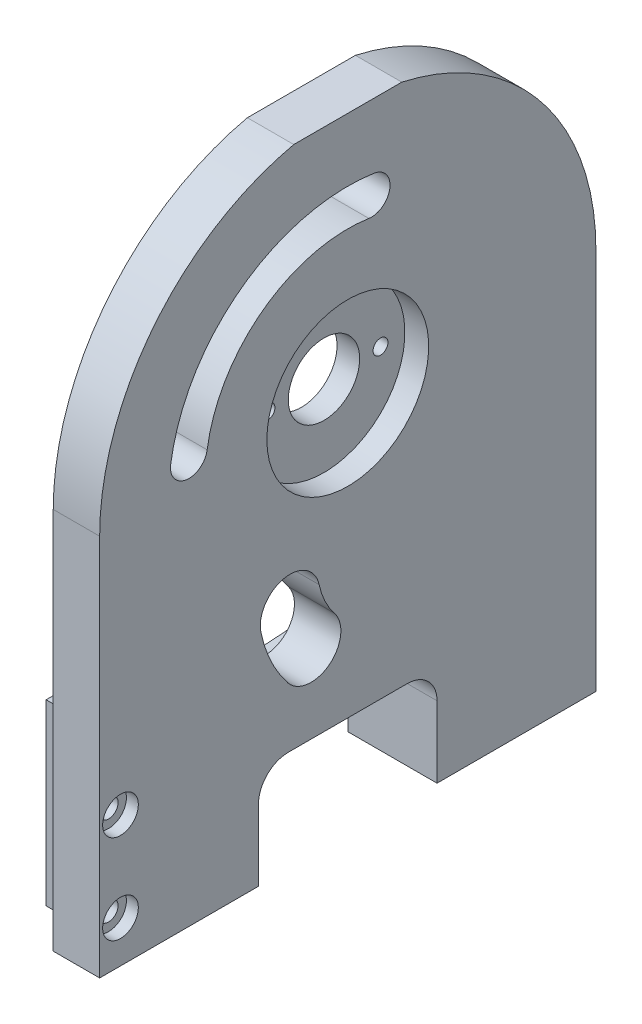
SolidWorks part; units mm, degrees
ref_plane "Front Plane" through (0, 0, 0) normal (0, 0, 1) x (1, 0, 0)
ref_plane "Top Plane" through (0, 0, 0) normal (0, 1, 0) x (1, 0, 0)
ref_plane "Right Plane" through (0, 0, 0) normal (1, 0, 0) x (0, 0, -1)
other "Configuration Table"
sketch "草图1" plane through (0, 0, 0) normal (0, 1, 0) x (1, 0, 0)
  line L0 (0, 0) -> (7.8, 0)
  line L1 (0, 0) -> (0, -83.4)
  line L2 (0, -83.4) -> (7.8, -83.4)
  line L3 (7.8, -83.4) -> (7.8, 0)
extrude "凸台-拉伸1" add sketch "草图1" along normal blind 105
sketch "草图2" plane through (0, 0, 0) normal (-1, 0, 0) x (0, 0, 1)
  line L0 (41.7, 0) -> (41.7, 105) construction
  line L1 (0, 0) -> (83.4, 0) construction
  line L2 (0, 105) -> (83.4, 105) construction
  line L3 (0, 64.3) -> (0, 105)
  line L4 (0, 105) -> (32.6226, 105)
  line L5 (83.4, 105) -> (83.4, 64.3)
  line L6 (50.7774, 105) -> (83.4, 105)
  arc A0 (83.4, 64.3) -> (50.7774, 105) centre (41.7, 64.3) ccw
  arc A1 (32.6226, 105) -> (0, 64.3) centre (41.7, 64.3) ccw
  dimension "D1" = 40.7
extrude "切除-拉伸1" cut sketch "草图2" against normal through all contours L3 L4 A1 | L6 L5 A0
sketch "草图3" plane through (0, 0, 0) normal (-1, 0, 0) x (0, 0, 1)
  line L0 (0, 64.3) -> (83.4, 64.3) construction
  circle A0 centre (41.7, 64.3) radius 6
  dimension "D1" = 12
extrude "切除-拉伸2" cut sketch "草图3" against normal through all
sketch "草图4" plane through (0, 0, 0) normal (-1, 0, 0) x (0, 0, 1)
  circle A0 centre (41.7, 64.3) radius 13.6
extrude "切除-拉伸3" cut sketch "草图4" against normal blind 4
sketch "草图5" plane through (4, 0, 0) normal (-1, 0, 0) x (0, 0, 1)
  line L0 (41.7, 64.3) -> (32.2, 64.3) construction
  line L1 (41.7, 64.3) -> (51.2, 64.3) construction
  circle A0 centre (32.2, 64.3) radius 1.25
  circle A1 centre (51.2, 64.3) radius 1.25
extrude "切除-拉伸4" cut sketch "草图5" against normal blind 4
sketch "草图6" plane through (7.8, 0, 0) normal (1, 0, 0) x (0, 0, -1)
  line L0 (-41.7, 64.3) -> (-41.7, 0) construction
  line L1 (-83.4, 0) -> (0, 0) construction
  line L2 (-83.4, 0) -> (0, 0)
  line L3 (0, 0) -> (0, 30)
  line L6 (-83.4, 30) -> (-69.2536, 30)
  line L7 (-83.4, 30) -> (-83.4, 0)
  line L9 (-14.1464, 30) -> (0, 30)
  arc A0 (-69.2536, 30) -> (-14.1464, 30) centre (-41.7, 61.3) ccw
  line M13 (-83.4, 64.3) -> (-83.4, 0)
  line M14 (-83.4, 0) -> (0, 0)
  line M15 (0, 0) -> (0, 64.3)
  dimension "D1" = 3
  dimension "D2" = 30
extrude "凸台-拉伸2" add sketch "草图6" along normal blind 7.2 contours A0 L0 L2 L9 M15 | L0 A0 L6 M13 M14
sketch "草图7" plane through (15, 0, 0) normal (1, 0, 0) x (0, 0, -1)
  line L0 (-83.4, 30) -> (-77.4, 30)
  line L1 (-83.4, 30) -> (-69.2536, 30) construction
  line L2 (-77.4, 30) -> (-77.4, 0)
  line L3 (-83.4, 0) -> (0, 0) construction
  line L4 (-77.4, 0) -> (-83.4, 0)
  line L5 (-83.4, 0) -> (-83.4, 30)
extrude "切除-拉伸5" cut sketch "草图7" against normal up to surface (7.2 mm away) up to face at (7.8, 64.3, 33.45)
sketch "草图8" plane through (0, 0, 0) normal (-1, 0, 0) x (0, 0, 1)
  line L1 (0, 0) -> (83.4, 0) construction
  line L2 (31.7, 17) -> (51.7, 17)
  line L3 (26.7, 12) -> (26.7, 0)
  line L4 (26.7, 0) -> (56.7, 0)
  line L5 (56.7, 0) -> (56.7, 12)
  arc A0 (56.7, 12) -> (51.7, 17) centre (51.7, 12) ccw
  arc A1 (31.7, 17) -> (26.7, 12) centre (31.7, 12) ccw
  point P7 (41.7, 17)
  dimension "D1" = 5
extrude "切除-拉伸6" cut sketch "草图8" against normal through all
sketch "草图9" plane through (0, 0, 0) normal (0, -1, 0) x (1, 0, 0)
  circle A0 centre (7.5, 73.4) radius 1.65
  circle A1 centre (7.5, 62.7) radius 1.65
  circle A2 centre (7.5, 20.7) radius 1.65
  circle A3 centre (7.5, 6) radius 1.65
extrude "切除-拉伸7" cut sketch "草图9" against normal blind 15
mirror "镜向2" about plane through (0, 0, 0) normal (1, 0, 0) of bodies 110
delete or keep bodies "实体-删除/保留 1" type delete bodies bodies 110
fillet "圆角1" radius 5 2 edges at (-11.4, 30, 69.2536) (-11.4, 30, 14.1464)
sketch "草图10" plane through (0, 0, 0) normal (1, 0, 0) x (0, 0, -1)
  line L0 (-41.7, 64.3) -> (-68.4, 68.3) construction
  line L1 (-68.4, 68.3) -> (-71.4658, 68.7593) construction
  line L2 (-41.7, 64.3) -> (-37.2407, 94.0658) construction
  line L3 (-41.7, 64.3) -> (-41.7, 87.0471) construction
  arc A0 (-37.2407, 94.0658) -> (-71.4658, 68.7593) centre (-41.7, 64.3) ccw
  arc A1 (-38.1593, 87.9342) -> (-65.3342, 67.8407) centre (-41.7, 64.3) ccw
  arc A2 (-37.2407, 94.0658) -> (-38.1593, 87.9342) centre (-37.7, 91) cw
  arc A3 (-71.4658, 68.7593) -> (-65.3342, 67.8407) centre (-68.4, 68.3) ccw
  dimension "D1" = 90
  dimension "D2" = 8.52
extrude "切除-拉伸8" cut sketch "草图10" against normal through all
sketch "草图13" plane through (0, 0, 0) normal (1, 0, 0) x (0, 0, -1)
  line L0 (-41.7, 64.3) -> (-47.8635, 30.2622) construction
  line L1 (-41.7, 64.3) -> (-51.4028, 37.7631) construction
  arc A0 (-51.4028, 37.7631) -> (-47.8635, 30.2622) centre (-33.7922, 41.4871) ccw construction
  arc A1 (-56.2946, 36.7287) -> (-51.7722, 27.1442) centre (-33.7922, 41.4871) ccw
  arc A2 (-46.5109, 38.7976) -> (-43.9548, 33.3802) centre (-33.7922, 41.4871) ccw
  arc A3 (-46.5109, 38.7976) -> (-56.2946, 36.7287) centre (-51.4028, 37.7631) ccw
  arc A4 (-51.7722, 27.1442) -> (-43.9548, 33.3802) centre (-47.8635, 30.2622) ccw
  point P3 (-50.0711, 33.806)
  dimension "D1" = 9.82
extrude "切除-拉伸10" cut sketch "草图13" against normal through all
sketch "草图14" plane through (0, 0, 0) normal (1, 0, 0) x (0, 0, -1)
  line L0 (-79.9, 0) -> (-83.4, 0) construction
  line L1 (-79.9, 0) -> (-79.9, 7) construction
  line L4 (-79.9, 7) -> (-79.9, 22) construction
  line L5 (-79.9, 22) -> (-79.9, 29.9966) construction
  circle A0 centre (-79.9, 7) radius 1.6
  circle A1 centre (-79.9, 22) radius 1.6
  dimension "D1" = 3.5
  dimension "D2" = 15
  dimension "D3" = 7
extrude "切除-拉伸11" cut sketch "草图14" against normal through all
sketch "草图15" plane through (0, 0, 0) normal (1, 0, 0) x (0, 0, -1)
  circle A0 centre (-79.9, 22) radius 3
  circle A1 centre (-79.9, 7) radius 3
extrude "切除-拉伸12" cut sketch "草图15" against normal blind 2
